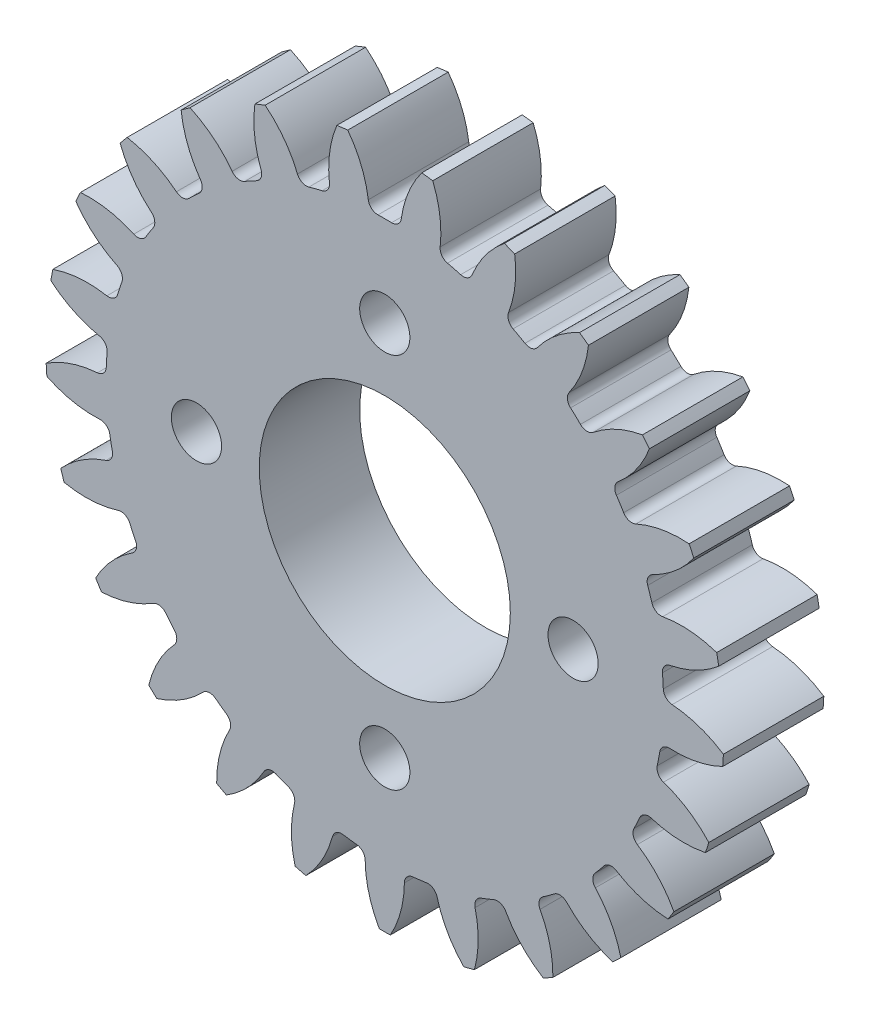
SolidWorks part; units mm, degrees
ref_plane "Front Plane" through (0, 0, 0) normal (0, 0, 1) x (1, 0, 0)
ref_plane "Top Plane" through (0, 0, 0) normal (0, 1, 0) x (1, 0, 0)
ref_plane "Right Plane" through (0, 0, 0) normal (1, 0, 0) x (0, 0, -1)
sketch "Sketch1" plane through (0, 0, 0) normal (0, 0, 1) x (1, 0, 0)
  line L0 (0, 0) -> (-18.1989, 0) construction
  line L1 (0, 0) -> (0, 8.2854) construction
  circle A0 centre (0, 0) radius 5
  circle A1 centre (0, 0) radius 13.5
  circle A2 centre (-7.5, 0) radius 1
  circle A6 centre (0, 7.5) radius 1
  circle A7 centre (7.5, 0) radius 1
  circle A8 centre (0, -7.5) radius 1
  point P19 (-0.125, -0.125)
  point P20 (0, 0)
  dimension "D1" = 10
  dimension "D2" = 27
  dimension "D3" = 2
  dimension "D4" = 7.5
  dimension "D5" = 4
extrude "Boss-Extrude1" add sketch "Sketch1" along normal blind 10
sketch "Sketch2" plane through (0, 0, 10) normal (0, 0, 1) x (1, 0, 0)
  line L0 (0, 0) -> (0, 13.5) construction
  line L1 (-0.6232, 11.0825) -> (0, 0) construction
  line L2 (0, 9.9064) -> (-3.5205, 19.5789) construction
  circle A0 centre (0, 0) radius 13.5 construction
  arc A1 (0.6232, 11.0825) -> (-0.6232, 11.0825) centre (0, 0) ccw
  arc A2 (0.9345, 12.465) -> (-0.9345, 12.465) centre (0, 0) ccw construction
  arc A3 (-1.4738, 13.4193) -> (-0.6232, 11.0825) centre (-4.9231, 10.8407) cw
  arc A4 (1.4738, 13.4193) -> (0.6232, 11.0825) centre (4.9231, 10.8407) ccw
  point P16 (-0.8762, 12.3136)
  dimension "D1" = 25
  dimension "D2" = 2.4
  dimension "D3" = 20
  dimension "D4" = 1.8708
extrude "Cut-Extrude3" cut sketch "Sketch2" against normal blind 10 and the other way through all flip side to cut
fillet "Fillet1" radius 0.38 2 edges at (0.6232, 11.0825, 5) (-0.6232, 11.0825, 5)
pattern_circular "CirPattern1" count 25 over 360 about axis through (0, 0, 0) along (0, 0, 1) of "Cut-Extrude3", "Fillet1"
sketch "Sketch5" plane through (0, 0, 10) normal (0, 0, 1) x (1, 0, 0)
  line L0 (0, 5) -> (0, 20) construction
  circle A0 centre (0, 0) radius 5 construction
  circle A1 centre (0, 20) radius 1.5
  dimension "D2" = 3
  dimension "D1" = 15
sketch "Sketch6" plane through (0, 0, 0) normal (0, 0, 1) x (1, 0, 0)
  line L0 (0, 0) -> (-20.4531, 0) construction
  circle A0 centre (0, 0) radius 12.5
  dimension "D1" = 25
sketch "Sketch9" plane through (0, 0, 0) normal (0, 0, 1) x (1, 0, 0)
  circle A0 centre (0, 0) radius 16.2134
extrude "Cut-Extrude9" cut sketch "Sketch9" against normal through all and the other way blind 6
equation "\"No. of teeth\"= 25"
equation "\"Module\"= 1mm"
equation "\"Bore Diameter\"= 10mm"
equation "\"Pressure Angle\"= 20"
equation "\"Outer Diameter\"= ( \"No. of teeth\" + 2 ) * \"Module\""
equation "\"Pitch Diameter\"= \"No. of teeth\" * \"Module\""
equation "\"Backlash\"= 0.3 * \"Module\""
equation "\"Are Length\"= ( ( \"Module\" * pi ) / 2 ) + \"Backlash\""
equation "\"Fillet Radius\"= 0.38 * \"Module\""
equation "\"Tooth Depth\"= IIF ( \"Module\" <= 1.25 , \"Module\" * 2.4 , \"Module\" * 2.25 )"
equation "\"D1@Sketch1\"=\"Bore Diameter\""
equation "\"D2@Sketch1\"=\"Outer Diameter\""
equation "\"D1@Sketch2\"=\"Pitch Diameter\""
equation "\"D2@Sketch2\"=\"Tooth Depth\""
equation "\"D3@Sketch2\"=\"Pressure Angle\""
equation "\"D4@Sketch2\"=\"Are Length\""
equation "\"D1@Fillet1\"=\"Fillet Radius\""
equation "\"D1@CirPattern1\"=\"No. of teeth\""
equation "\"D1@Sketch6\"=\"Pitch Diameter\""
equation "\"D4@Sketch1\"=15/2"
